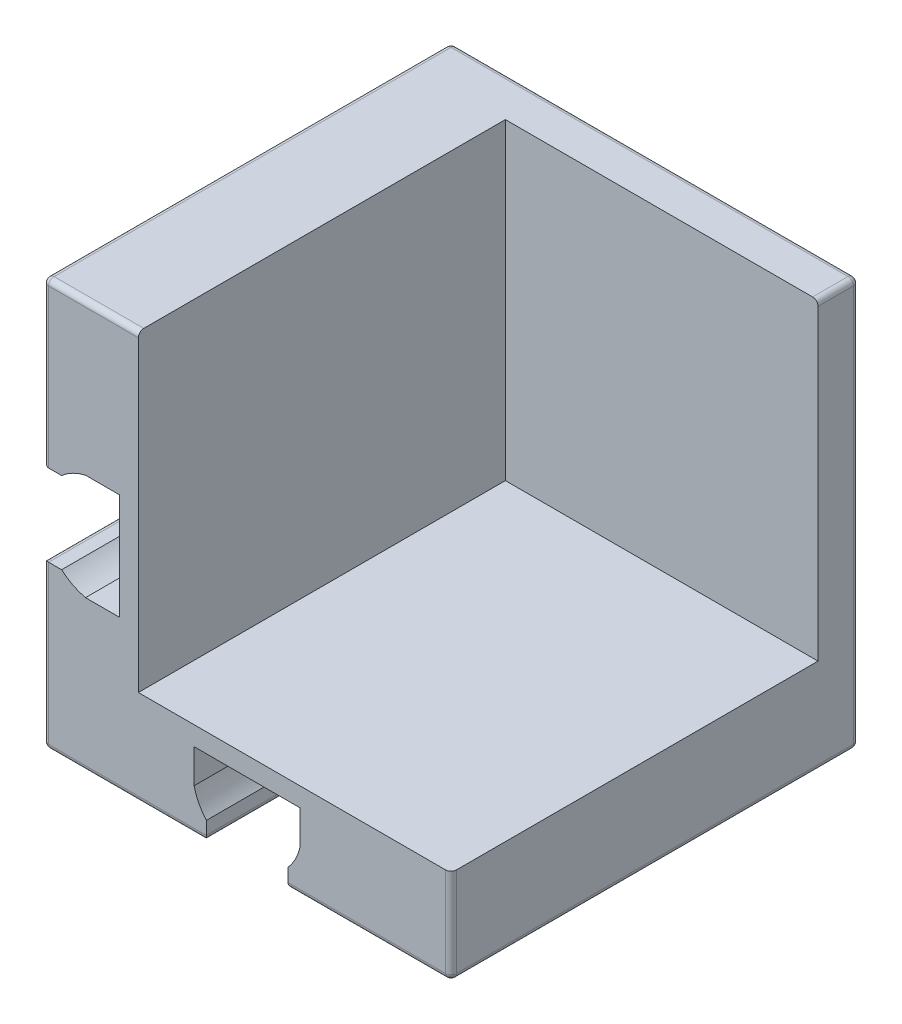
SolidWorks part; units mm, degrees
ref_plane "前视基准面" through (0, 0, 0) normal (0, 0, 1) x (1, 0, 0)
ref_plane "上视基准面" through (0, 0, 0) normal (0, 1, 0) x (1, 0, 0)
ref_plane "右视基准面" through (0, 0, 0) normal (1, 0, 0) x (0, 0, -1)
sketch "草图1" plane through (0, 0, 0) normal (0, 0, 1) x (1, 0, 0)
  line L1 (-7.5, 0) -> (7.5, 0)
  line L2 (-7.5, 0) -> (-7.5, 15)
  line L3 (-7.5, 15) -> (7.5, 15)
  line L4 (7.5, 0) -> (7.5, 15)
extrude "凸台-拉伸1" add sketch "草图1" against normal blind 15
sketch "草图2" plane through (0, 15, 0) normal (0, 1, 0) x (-1, 0, 0)
  line L1 (4, -13.5) -> (-7.5, -13.5)
  line L2 (4, -13.5) -> (4, 0)
  line L3 (4, 0) -> (-7.5, 0)
  line L4 (-7.5, -13.5) -> (-7.5, 0)
extrude "切除-拉伸1" cut sketch "草图2" against normal blind 11.5
sketch "草图3" plane through (0, 0, 0) normal (0, 0, 1) x (1, 0, 0)
  line L0 (-1.5, 0) -> (-1.5, 0.6771)
  line L1 (-7.5, 0) -> (7.5, 0) construction
  line L2 (1.5, 0) -> (1.5, 0.6771)
  line L3 (-1.5, 0) -> (1.5, 0)
  line L4 (-1.95, 2.8) -> (1.95, 2.8)
  line L5 (-1.95, 2.8) -> (-1.95, 1.5556)
  line L6 (1.95, 2.8) -> (1.95, 1.5556)
  line L7 (-7.5, 9) -> (-7.5, 6)
  line L8 (-4.7, 9.45) -> (-5.9444, 9.45)
  line L9 (-7.5, 9) -> (-6.8229, 9)
  line L10 (-7.5, 6) -> (-6.8229, 6)
  line L11 (-4.7, 5.55) -> (-5.9444, 5.55)
  line L12 (-4.7, 9.45) -> (-4.7, 5.55)
  arc A0 (-1.95, 1.5556) -> (-1.5, 0.6771) centre (0, 2) ccw
  arc A1 (1.5, 0.6771) -> (1.95, 1.5556) centre (0, 2) ccw
  arc A2 (-5.9444, 9.45) -> (-6.8229, 9) centre (-5.5, 7.5) ccw
  arc A3 (-6.8229, 6) -> (-5.9444, 5.55) centre (-5.5, 7.5) ccw
extrude "切除-拉伸2" cut sketch "草图3" against normal blind 9.45
sketch "草图4" plane through (0, 0, -15) normal (0, 0, -1) x (-1, 0, 0)
  line L1 (-1.5, 6) -> (1.5, 6)
  line L2 (-1.5, 6) -> (-1.5, 9)
  line L3 (-1.5, 9) -> (1.5, 9)
  line L4 (1.5, 6) -> (1.5, 9)
extrude "凸台-拉伸2" add sketch "草图4" along normal blind 1
sketch "草图5" plane through (0, 9, 0) normal (0, 1, 0) x (-1, 0, 0)
  line L0 (1.95, -17.5) -> (-1.95, -17.5)
  line L1 (1.95, -17.5) -> (1.95, -16.5556)
  line L2 (-1.95, -17.5) -> (-1.95, -16.5556)
  line L4 (1.5, -16) -> (1.5, -15) construction
  line L5 (1.5, -15.6771) -> (-1.5, -15.6771)
  arc A0 (1.95, -16.5556) -> (1.5, -15.6771) centre (0, -17) ccw
  arc A3 (-1.5, -15.6771) -> (-1.95, -16.5556) centre (0, -17) ccw
extrude "凸台-拉伸3" add sketch "草图5" along normal blind 2 and the other way blind 4
sketch "草图6" plane through (1.95, 0, 0) normal (1, 0, 0) x (0, 0, -1)
  line L0 (17.5, 9.45) -> (16.5556, 9.45)
  line L1 (17.5, 5.55) -> (16.5556, 5.55)
  line L2 (17.5, 11) -> (17.5, 9.45)
  line L3 (17.5, 5) -> (15.6771, 5)
  line L4 (15.6771, 5) -> (15.6771, 6)
  line L5 (15.6771, 9) -> (15.6771, 11)
  line L6 (15.6771, 11) -> (17.5, 11)
  line L7 (17.5, 5.5635) -> (17.5, 5)
  arc A0 (15.6771, 6) -> (16.5556, 5.55) centre (17, 7.5) ccw
  arc A1 (16.5556, 9.45) -> (15.6771, 9) centre (17, 7.5) ccw
  line M1 (17.5, 5) -> (17.5, 11)
  line M2 (17.5, 11) -> (16.5556, 11)
  line M3 (16.5556, 11) -> (16.5556, 5)
  line M4 (16.5556, 5) -> (17.5, 5)
extrude "切除-拉伸3" cut sketch "草图6" against normal up to next contours A0 L4 L3 M3 | L1 M1 M3 M4 | L0 M1 M2 M3 | A1 L6 L5 M3
fillet "圆角1" radius 0.1 4 edges at (0, 5.55, -17.5) (1.95, 7.5, -17.5) (0, 9.45, -17.5) (-1.95, 7.5, -17.5)
fillet "圆角2" radius 0.2 20 edges at (4.5, 0, 0) (7.5, 0, -7.5) (0, 0, -15) (-4.5, 0, 0) (-1.5, 0, -4.725) (0, 0, -9.45) (1.5, 0, -4.725) (-7.5, 3, 0) (-7.5, 0, -7.5) (-7.5, 7.5, -15) (-7.5, 15, -7.5) (-7.5, 12, 0) (-7.5, 9, -4.725) (-7.5, 7.5, -9.45) (-7.5, 6, -4.725) (7.5, 7.5, -15) (0, 15, -15) (7.5, 1.75, 0) (7.5, 15, -14.25) (-5.75, 15, 0)
